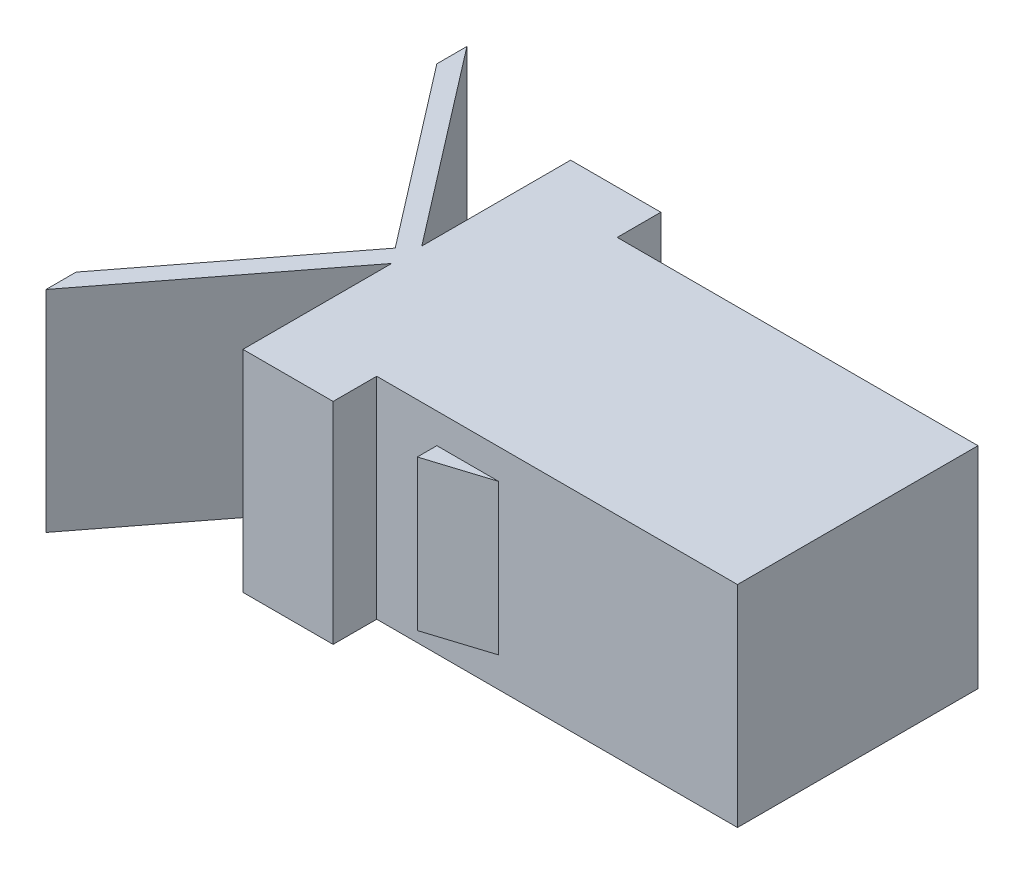
SolidWorks part; units mm, degrees
ref_plane "前视基准面" through (0, 0, 0) normal (0, 0, 1) x (1, 0, 0)
ref_plane "上视基准面" through (0, 0, 0) normal (0, 1, 0) x (1, 0, 0)
ref_plane "右视基准面" through (0, 0, 0) normal (1, 0, 0) x (0, 0, -1)
other "Configuration Table"
sketch "草图1" plane through (0, 0, 0) normal (0, 1, 0) x (1, 0, 0)
  line L1 (0, 0) -> (12, 0)
  line L2 (0, 0) -> (0, 8)
  line L3 (0, 8) -> (12, 8)
  line L4 (12, 0) -> (12, 8)
  dimension "D1" = 12
  dimension "D2" = 8
extrude "凸台-拉伸1" add sketch "草图1" along normal blind 7
sketch "草图2" plane through (0, 7, 0) normal (0, 1, 0) x (1, 0, 0)
  line L0 (0, 8) -> (0, 0) construction
  line L1 (0, -1.45) -> (-3, -1.45)
  line L2 (0, -1.45) -> (0, 9.45)
  line L3 (0, 9.45) -> (-3, 9.45)
  line L4 (-3, -1.45) -> (-3, 9.45)
  line L5 (0, 4) -> (-3, 4)
  line M6 (0, 8) -> (0, 0)
  dimension "D1" = 3
  dimension "D2" = 10.9
extrude "凸台-拉伸2" add sketch "草图2" against normal up to surface (7 mm away) contours L2 L5 L4 L1 | L5 L2 L3 L4 M6 up to face at (6, 0, -4)
sketch "草图3" plane through (0, 7, 0) normal (0, 1, 0) x (1, 0, 0)
  line L0 (-3, 4.5) -> (-8, 11)
  line L1 (-3, -1.45) -> (-3, 9.45) construction
  line L2 (-8, 11) -> (-8, 10)
  line L3 (-8, 10) -> (-3, 3.5)
  line L4 (-3, 4.5) -> (-8, -2)
  line L5 (-8, -2) -> (-8, -3)
  line L6 (-8, -3) -> (-3, 3.5)
  line L7 (-3, 4.5) -> (-3, 3.5)
  line L8 (-3, 4.5) -> (-3, 3.5)
  point P8 (-3, 4.7513)
  point P9 (-3, 4)
  point P10 (-8.8881, 3.6392)
  point P11 (-10.1856, 10.0709)
  point P12 (-8.6657, 12.7215)
  point P13 (-9.2959, 0.377)
  point P14 (0, 0)
  point P15 (-9.772, 9.8327)
  point P16 (-10.922, 10)
  line M12 (-3, 9.45) -> (-3, -1.45)
  dimension "D1" = 14
  dimension "D2" = 1
  dimension "D3" = 5
extrude "凸台-拉伸5" add sketch "草图3" against normal up to surface (7 mm away) contours L4 L0 L2 L3 | L5 L6 L3 L4 | L4 L3 M12 up to face at (2.25, 0, -4)
sketch "草图4" plane through (0, 7, 0) normal (0, 1, 0) x (1, 0, 0)
  line L0 (2, 8) -> (2, 8.65)
  line L1 (12, 8) -> (0, 8) construction
  line L2 (2, 8.65) -> (3, 8)
  line L3 (2, 0) -> (2, -0.65)
  line L4 (0, 0) -> (12, 0) construction
  line L5 (2, -0.65) -> (4.0581, 0)
  line L6 (2, 8) -> (3, 8)
  line L7 (4.0581, 0) -> (2, 0)
  line L8 (0, 9.45) -> (0, 8) construction
  point P12 (2, 8.7781)
  point P13 (3.591, 8)
  dimension "D1" = 2
  dimension "D2" = 9.3
  dimension "D3" = 1
extrude "凸台-拉伸6" add sketch "草图4" against normal offset from surface (5 mm away) 1 from offset 1 up to face at (-1.559, 0, -4) offset against normal yes
